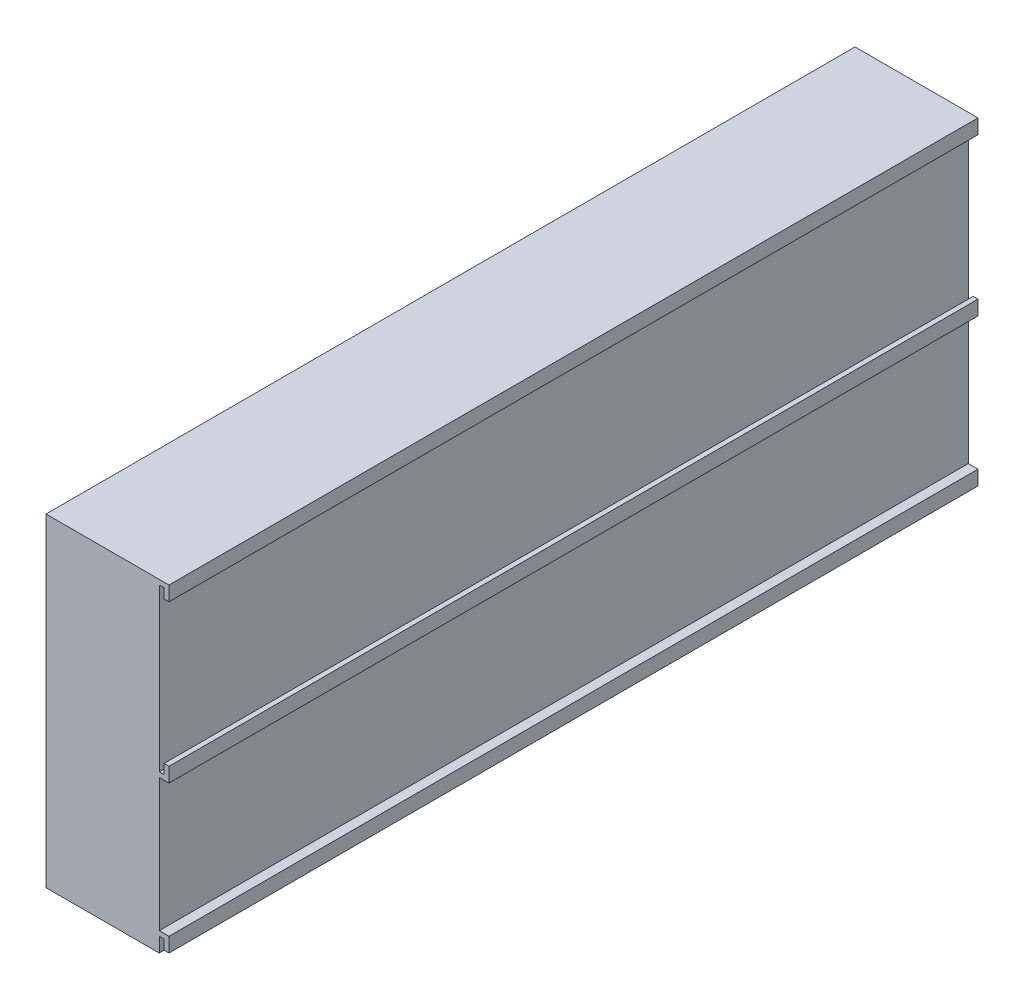
SolidWorks part; units mm, degrees
ref_plane "Alzado" through (0, 0, 0) normal (0, 0, 1) x (1, 0, 0)
ref_plane "Planta" through (0, 0, 0) normal (0, 1, 0) x (1, 0, 0)
ref_plane "Vista lateral" through (0, 0, 0) normal (1, 0, 0) x (0, 0, -1)
sketch "Croquis1" plane through (0, 0, 0) normal (0, 0, 1) x (1, 0, 0)
  line L0 (17.5, 50) -> (20.5, 50)
  line L1 (-17.5, -50) -> (17.5, -50)
  line L2 (-17.5, -50) -> (-17.5, 50)
  line L3 (-17.5, 50) -> (17.5, 50)
  line L4 (17.5, -50) -> (17.5, -45.5)
  line L5 (-17.5, -50) -> (17.5, 50) construction
  line L6 (-17.5, 50) -> (17.5, -50) construction
  line L7 (20.5, 50) -> (20.5, 45.5)
  line L8 (20.5, 45.5) -> (19, 45.5)
  line L9 (19, 45.5) -> (19, 48.5)
  line L10 (19, 48.5) -> (17.5, 48.5)
  line L11 (17.5, -44) -> (20.5, -44)
  line L12 (20.5, -44) -> (20.5, -48.5)
  line L13 (20.5, -48.5) -> (19, -48.5)
  line L14 (19, -48.5) -> (19, -45.5)
  line L15 (19, -45.5) -> (17.5, -45.5)
  line L16 (17.5, -3) -> (20.5, -3)
  line L17 (20.5, -3) -> (20.5, 1.5)
  line L18 (20.5, 1.5) -> (19, 1.5)
  line L19 (19, 1.5) -> (19, -1.5)
  line L20 (19, -1.5) -> (17.5, -1.5)
  line L21 (17.5, -1.5) -> (17.5, 48.5)
  line L22 (17.5, -44) -> (17.5, -3)
  point P0 (0, 0)
  point P20 (18.25, -45.5)
  dimension "D1" = 35
  dimension "D2" = 100
  dimension "D3" = 1.5
  dimension "D4" = 3
  dimension "D5" = 1.5
  dimension "D6" = 3
  dimension "D7" = 3
  dimension "D8" = 1.5
  dimension "D9" = 1.5
  dimension "D10" = 1.5
  dimension "D11" = 3
  dimension "D12" = 1.5
  dimension "D13" = 1.5
  dimension "D14" = 3
  dimension "D15" = 1.5
  dimension "D16" = 3
extrude "Saliente-Extruir1" add sketch "Croquis1" along normal blind 250
